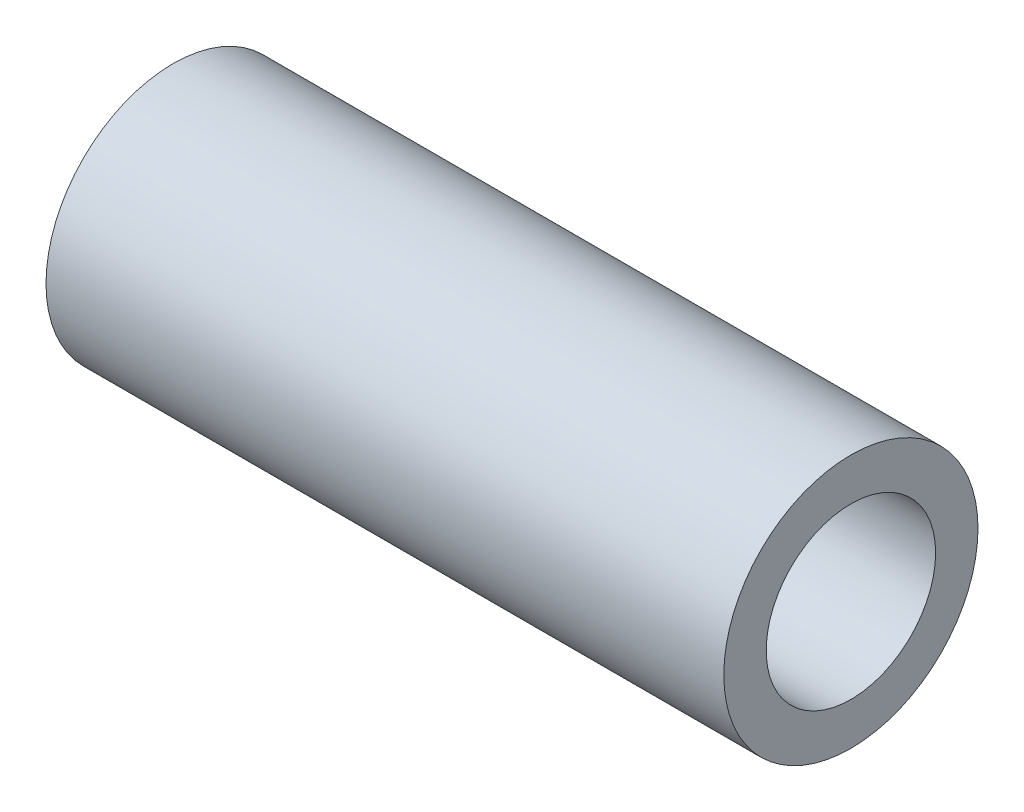
SolidWorks part; units mm, degrees
ref_plane "Front Plane" through (0, 0, 0) normal (0, 0, 1) x (1, 0, 0)
ref_plane "Top Plane" through (0, 0, 0) normal (0, 1, 0) x (1, 0, 0)
ref_plane "Right Plane" through (0, 0, 0) normal (1, 0, 0) x (0, 0, -1)
sketch "Sketch1" plane through (0, 0, 0) normal (1, 0, 0) x (0, 0, -1)
  circle A0 centre (0, 0) radius 3.175
  circle A1 centre (0, 0) radius 4.7625
  dimension "D1" = 6.35
  dimension "D2" = 9.525
extrude "Boss-Extrude1" add sketch "Sketch1" along normal blind 25.4
